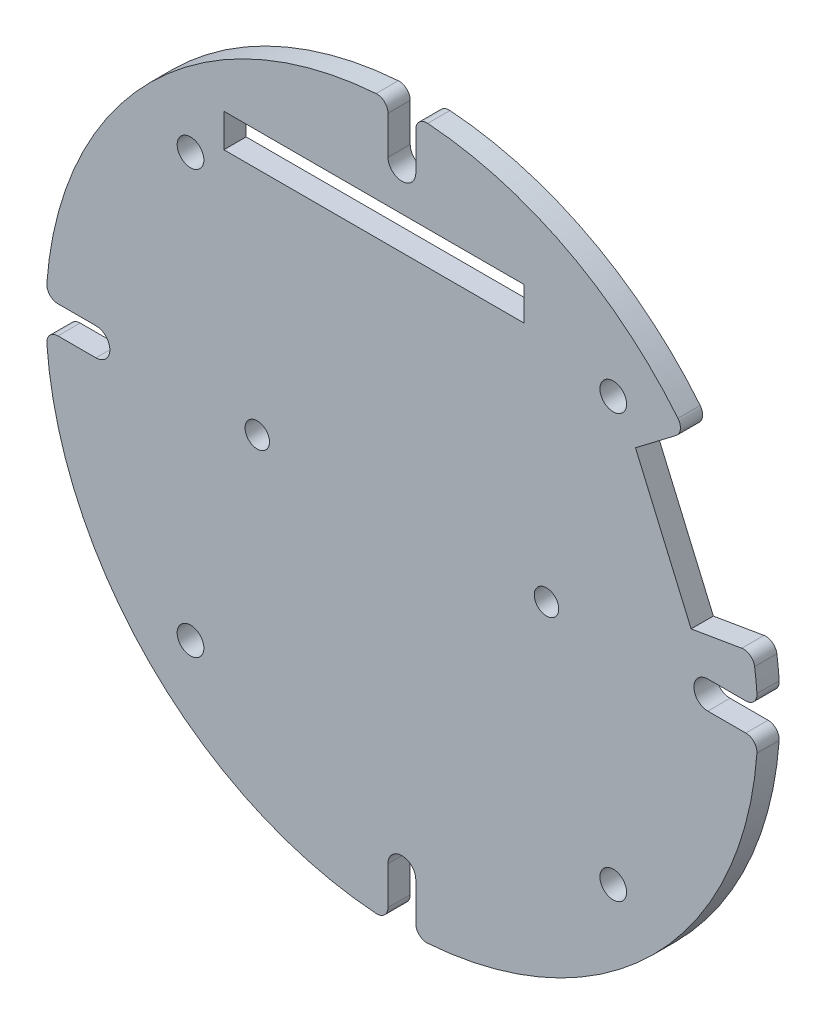
SolidWorks part; units mm, degrees
ref_plane "정면" through (0, 0, 0) normal (0, 0, 1) x (1, 0, 0)
ref_plane "윗면" through (0, 0, 0) normal (0, 1, 0) x (1, 0, 0)
ref_plane "우측면" through (0, 0, 0) normal (1, 0, 0) x (0, 0, -1)
sketch "스케치1" plane through (0, 0, 0) normal (0, 0, 1) x (1, 0, 0)
  circle A0 centre (0, 0) radius 32
  dimension "D1" = 64
extrude "보스-돌출1" add sketch "스케치1" along normal blind 2
sketch "스케치2" plane through (0, 0, 2) normal (0, 0, 1) x (1, 0, 0)
  line L0 (0, 19) -> (0, -19) construction
  line L1 (-6.3087, 0) -> (14.8794, 0) construction
  line L2 (0, -27.5) -> (0, -31.9756) construction
  line L3 (1.25, -27.5) -> (1.25, -31.9756)
  line L4 (-1.25, -27.5) -> (-1.25, -31.9756)
  line L5 (27.5, 0) -> (32, 0) construction
  line L6 (27.5, 1.25) -> (32, 1.25)
  line L7 (27.5, -1.25) -> (32, -1.25)
  line L8 (-27.5, 0) -> (-32, 0) construction
  line L9 (-27.5, -1.25) -> (-32, -1.25)
  line L10 (-27.5, 1.25) -> (-32, 1.25)
  line L23 (0, 27.5) -> (0, 32) construction
  line L24 (-1.25, 27.5) -> (-1.25, 32)
  line L25 (1.25, 27.5) -> (1.25, 32)
  arc A0 (27.5, 1.25) -> (27.5, -1.25) centre (27.5, 0) ccw
  circle A3 centre (-13, 0) radius 1.1
  circle A4 centre (13, 0) radius 1.1
  arc A5 (1.25, -27.5) -> (-1.25, -27.5) centre (0, -27.5) ccw
  arc A6 (-1.25, -31.9756) -> (1.25, -31.9756) centre (0, -31.9756) ccw
  arc A7 (32, -1.25) -> (32, 1.25) centre (32, 0) ccw
  arc A8 (-27.5, -1.25) -> (-27.5, 1.25) centre (-27.5, 0) ccw
  arc A9 (-32, 1.25) -> (-32, -1.25) centre (-32, 0) ccw
  arc A11 (-1.25, 27.5) -> (1.25, 27.5) centre (0, 27.5) ccw
  arc A12 (1.25, 32) -> (-1.25, 32) centre (0, 32) ccw
  circle A14 centre (0, 0) radius 32 construction
  point P3 (29.75, 0)
  point P15 (0, -29.7378)
  point P27 (-29.75, 0)
  point P51 (0, 29.75)
  dimension "D3" = 1.25
  dimension "D4" = 2.2
  dimension "D1" = 55
  dimension "D2" = 55
  dimension "D5" = 26
extrude "컷-돌출1" cut sketch "스케치2" against normal through all
sketch "스케치3" plane through (0, 0, 2) normal (0, 0, 1) x (1, 0, 0)
  line L1 (-21, 21) -> (21, 21) construction
  line L2 (-21, 21) -> (-21, -21) construction
  line L3 (-21, -21) -> (21, -21) construction
  line L4 (21, 21) -> (21, -21) construction
  line L5 (-21, 21) -> (21, -21) construction
  line L6 (-21, -21) -> (21, 21) construction
  point P0 (0, 0)
  dimension "D1" = 42
sketch "스케치4" plane through (0, 0, 2) normal (0, 0, 1) x (1, 0, 0)
  line L1 (-19, 19) -> (19, 19) construction
  line L2 (-19, 19) -> (-19, -19) construction
  line L3 (-19, -19) -> (19, -19) construction
  line L4 (19, 19) -> (19, -19) construction
  line L5 (-19, 19) -> (19, -19) construction
  line L6 (-19, -19) -> (19, 19) construction
  point P0 (0, 0)
  dimension "D1" = 38
hole_wizard "M2 여유 구멍1" positions "3D스케치1" profile "스케치5" hole size "M2" standard "Ansi Metric"
sketch3d "3D스케치1"
  point P0 (-19, 19, 2)
  point P3 (19, 19, 2)
  point P6 (19, -19, 2)
  point P9 (-19, -19, 2)
sketch "스케치5" plane through (-19, 19, 2) normal (1, 0, 0) x (0, -1, 0)
  line L0 (0, 0) -> (0, 4.221)
  line L1 (0, 4.221) -> (1.2, 3.5)
  line L2 (1.2, 3.5) -> (1.2, 0)
  line L5 (1.2, 0) -> (0, 0)
  line L10 (0, 4.221) -> (-1.2, 3.5) construction
  line L11 (0, -6.35) -> (0, 107.95) construction
  dimension "구멍 지름" = 2.4
  dimension "구멍 깊이" = 3.5
  dimension "드릴 각도" = 118
sketch "스케치6" plane through (0, 0, 2) normal (0, 0, 1) x (1, 0, 0)
  line L0 (-16, 20.7) -> (11, 23.7) construction
  line L1 (11, 22.2) -> (28.5451, 22.2) construction
  line L5 (0, 0) -> (0, -37.4185) construction
  line L7 (-16, 23.7) -> (11, 23.7)
  line L8 (-16, 23.7) -> (-16, 20.7)
  line L9 (-16, 20.7) -> (11, 20.7)
  line L10 (11, 23.7) -> (11, 20.7)
  line L11 (21, 21) -> (21, -21) construction
  circle A0 centre (25, 22.2) radius 1.1
  point P4 (-2.5, 22.2)
  dimension "D2" = 2.2
  dimension "D1" = 4
  dimension "D3" = 27
  dimension "D4" = 2.5
  dimension "D5" = 22.2
  dimension "D6" = 3
extrude "컷-돌출2" cut sketch "스케치6" against normal through all
sketch "Sketch1" plane through (0, 0, 2) normal (0, 0, 1) x (1, 0, 0)
  line L0 (21, 16) -> (30.2553, 23.0516)
  line L1 (26, 4.4) -> (39.7658, 6.7296)
  line L2 (21, 16) -> (26, 4.4)
  line L3 (39.7658, 6.7296) -> (30.2553, 23.0516)
  line L4 (0, 0) -> (38.2863, 0) construction
  line L5 (-21, 21) -> (21, -21) construction
  dimension "D1" = 26
  dimension "D4" = 16
  dimension "D2" = 4.4
  dimension "D3" = 21
extrude "Cut-Extrude1" cut sketch "Sketch1" against normal blind 10
fillet "Fillet2" radius 1 10 edges at (1.25, 31.9756, 1) (-1.25, 31.9756, 1) (31.5514, 5.3395, 1) (25.4538, 19.3934, 1) (-31.9756, -1.25, 1) (-31.9756, 1.25, 1) (-1.25, -31.9756, 1) (1.25, -31.9756, 1) (31.9756, -1.25, 1) (31.9756, 1.25, 1)
equation "\"D3@스케치2\"=2.5/2"
